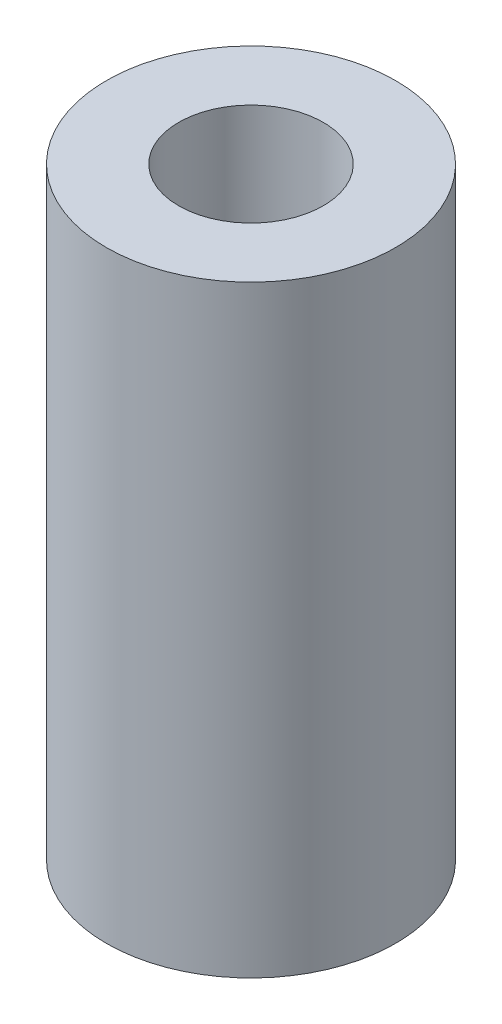
SolidWorks part; units mm, degrees
ref_plane "Front Plane" through (0, 0, 0) normal (0, 0, 1) x (1, 0, 0)
ref_plane "Top Plane" through (0, 0, 0) normal (0, 1, 0) x (1, 0, 0)
ref_plane "Right Plane" through (0, 0, 0) normal (1, 0, 0) x (0, 0, -1)
sketch "Sketch1" plane through (0, 0, 0) normal (0, 1, 0) x (1, 0, 0)
  circle A0 centre (0, 0) radius 3
  circle A1 centre (0, 0) radius 6
  dimension "D1" = 6
  dimension "D2" = 12
extrude "Boss-Extrude1" add sketch "Sketch1" along normal blind 25
